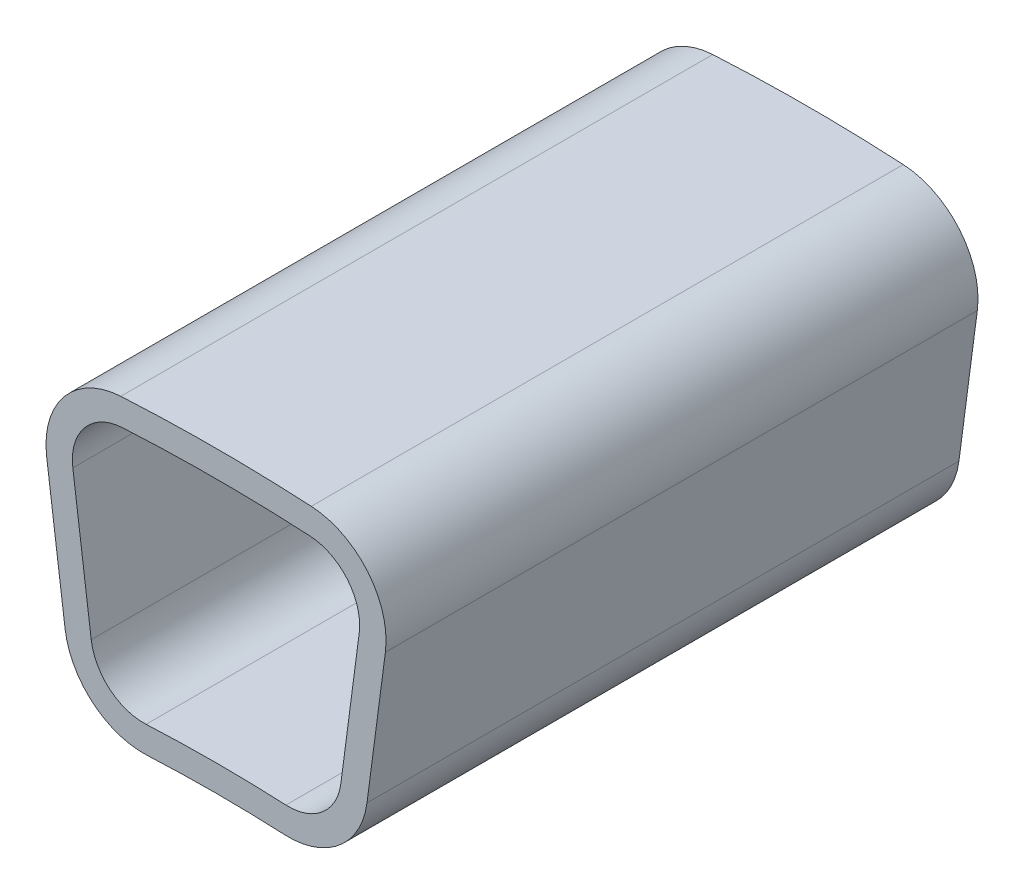
SolidWorks part; units mm, degrees
material "Copper"
ref_plane "Front Plane" through (0, 0, 0) normal (0, 0, 1) x (1, 0, 0)
ref_plane "Top Plane" through (0, 0, 0) normal (0, 1, 0) x (1, 0, 0)
ref_plane "Right Plane" through (0, 0, 0) normal (1, 0, 0) x (0, 0, -1)
sketch "Sketch1" plane through (0, 0, 0) normal (0, 0, 1) x (1, 0, 0)
  line L0 (8.5818, 84.3384) -> (9.6268, 92.2757)
  line L1 (-9.6268, 92.2757) -> (-8.5818, 84.3384)
  line L2 (-8.1396, 92.4715) -> (-7.0946, 84.5341)
  line L3 (7.0946, 84.5341) -> (8.1396, 92.4715)
  line L4 (-8.1396, 92.4715) -> (-7.0946, 84.5341)
  line L5 (7.0946, 84.5341) -> (8.1396, 92.4715)
  arc A0 (9.6268, 92.2757) -> (5.4152, 97.3561) centre (5.1652, 92.863) ccw
  arc A1 (5.4152, 97.3561) -> (-5.4152, 97.3561) centre (0, 0) ccw
  arc A2 (-5.4152, 97.3561) -> (-9.6268, 92.2757) centre (-5.1652, 92.863) ccw
  arc A3 (-8.5818, 84.3384) -> (-3.9022, 80.431) centre (-4.1203, 84.9257) ccw
  arc A4 (3.9022, 80.431) -> (-3.9022, 80.431) centre (0, 0) ccw
  arc A5 (3.9022, 80.431) -> (8.5818, 84.3384) centre (4.1203, 84.9257) ccw
  arc A6 (8.1396, 92.4715) -> (5.3319, 95.8584) centre (5.1652, 92.863) ccw
  arc A7 (5.3319, 95.8584) -> (-5.3319, 95.8584) centre (0, 0) ccw
  arc A8 (-5.3319, 95.8584) -> (-8.1396, 92.4715) centre (-5.1652, 92.863) ccw
  arc A9 (-7.0946, 84.5341) -> (-3.9749, 81.9292) centre (-4.1203, 84.9257) ccw
  arc A10 (3.9749, 81.9292) -> (-3.9749, 81.9292) centre (0, 0) ccw
  arc A11 (3.9749, 81.9292) -> (7.0946, 84.5341) centre (4.1203, 84.9257) ccw
  arc A12 (8.1396, 92.4715) -> (5.3319, 95.8584) centre (5.1652, 92.863) ccw
  arc A13 (5.3319, 95.8584) -> (-5.3319, 95.8584) centre (0, 0) ccw
  arc A14 (-5.3319, 95.8584) -> (-8.1396, 92.4715) centre (-5.1652, 92.863) ccw
  arc A15 (-7.0946, 84.5341) -> (-3.9749, 81.9292) centre (-4.1203, 84.9257) ccw
  arc A16 (3.9749, 81.9292) -> (-3.9749, 81.9292) centre (0, 0) ccw
  arc A17 (3.9749, 81.9292) -> (7.0946, 84.5341) centre (4.1203, 84.9257) ccw
  dimension "D1" = 0
  dimension "D2" = 1.5
extrude "Boss-Extrude1" add sketch "Sketch1" along normal up to surface (33.65 mm away)
